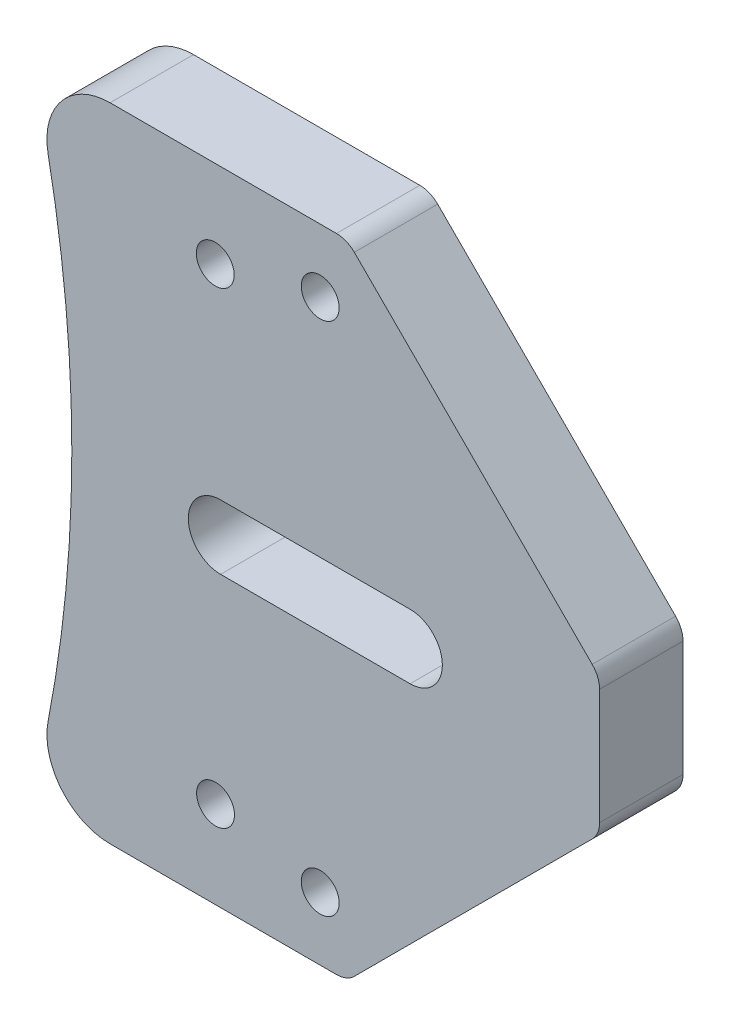
SolidWorks part; units mm, degrees
ref_plane "Front Plane" through (0, 0, 0) normal (0, 0, 1) x (1, 0, 0)
ref_plane "Top Plane" through (0, 0, 0) normal (0, 1, 0) x (1, 0, 0)
ref_plane "Right Plane" through (0, 0, 0) normal (1, 0, 0) x (0, 0, -1)
sketch "Model" plane through (0, 0, 0) normal (0, 0, 1) x (1, 0, 0)
  line L0 (3.0858, -24.8142) -> (21.9142, -5.9858)
  line L1 (21.9142, 5.9858) -> (3.0858, 24.8142)
  line L2 (-7.5, -2.5527) -> (7.5, -2.5527)
  line L3 (7.5, 2.5527) -> (-7.5, 2.5527)
  line L4 (-16.244, -25.4) -> (1.6716, -25.4)
  line L5 (1.6716, 25.4) -> (-16.244, 25.4)
  line L6 (22.5, -4.5716) -> (22.5, 4.5716)
  circle A0 centre (0.3858, 20.4) radius 1.5
  circle A1 centre (0.3858, -20.4) radius 1.5
  circle A2 centre (-7.9226, 18.5) radius 1.5
  circle A3 centre (-7.8991, -18.5) radius 1.5
  arc A4 (22.5, 4.5716) -> (21.9142, 5.9858) centre (20.5, 4.5716) ccw
  arc A5 (21.9142, -5.9858) -> (22.5, -4.5716) centre (20.5, -4.5716) ccw
  arc A6 (1.6716, -25.4) -> (3.0858, -24.8142) centre (1.6716, -23.4) ccw
  arc A7 (-21.1515, -19.4432) -> (-16.244, -25.4) centre (-16.244, -20.4) ccw
  arc A8 (-21.1515, -19.4432) -> (-21.1515, 19.4432) centre (-120.8738, 0) ccw
  arc A9 (-16.244, 25.4) -> (-21.1515, 19.4432) centre (-16.244, 20.4) ccw
  arc A10 (3.0858, 24.8142) -> (1.6716, 25.4) centre (1.6716, 23.4) ccw
  arc A11 (-7.5, 2.5527) -> (-7.5, -2.5527) centre (-7.5, 0) ccw
  arc A12 (7.5, -2.5527) -> (7.5, 2.5527) centre (7.5, 0) ccw
extrude "Boss-Extrude1" add sketch "Model" along normal blind 6.6
